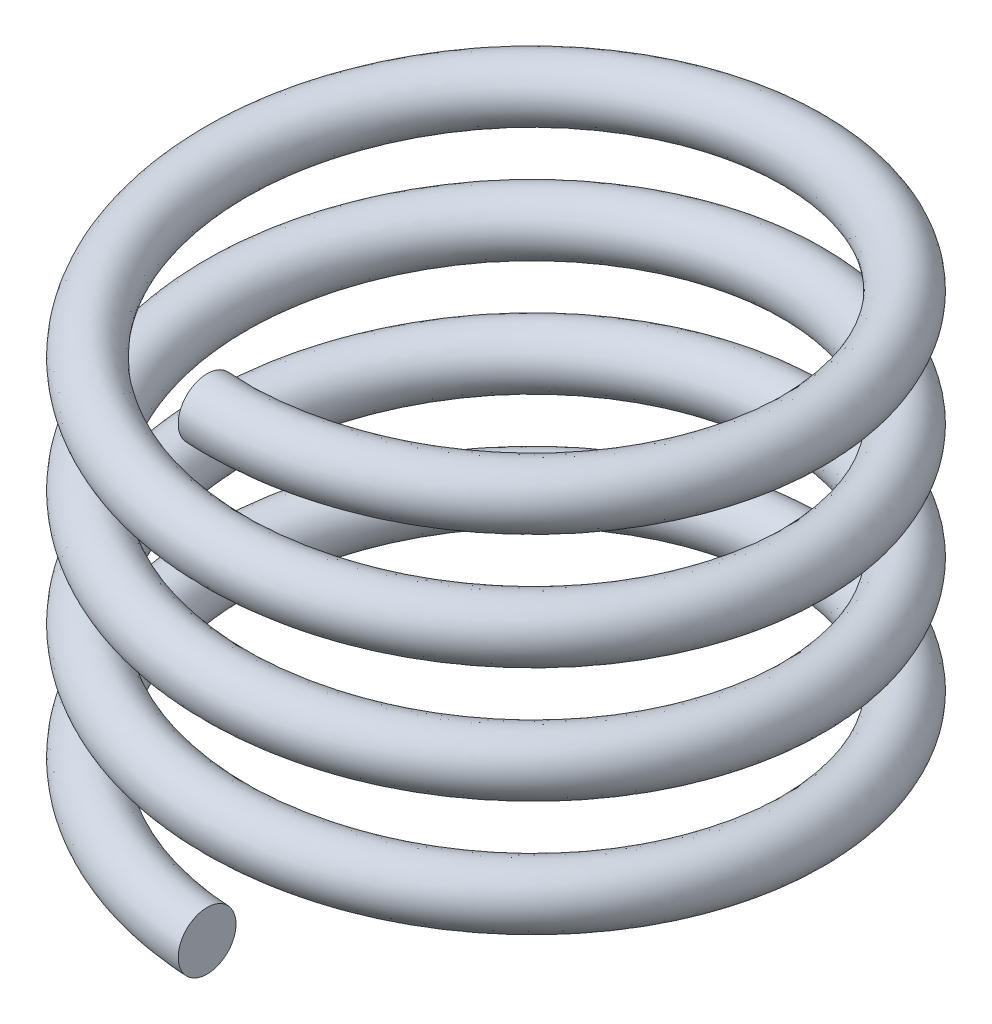
SolidWorks part; units mm, degrees
ref_plane "Front Plane" through (0, 0, 0) normal (0, 0, 1) x (1, 0, 0)
ref_plane "Top Plane" through (0, 0, 0) normal (0, 1, 0) x (1, 0, 0)
ref_plane "Right Plane" through (0, 0, 0) normal (1, 0, 0) x (0, 0, -1)
sketch "Sketch2" plane through (0, 0, 0) normal (0, 1, 0) x (1, 0, 0)
  circle A0 centre (0, 0) radius 6.35
  dimension "D1" = 12.7
curve "Helix/Spiral2" pitch 2.54 height 10.16 turns 4
sketch "Sketch3" plane through (0, 0, 0) normal (1, 0, 0) x (0, 0, -1)
  circle A0 centre (-6.35, 0) radius 0.635
  spline S0 degree 3 poles (-6.35, 0) (-6.35, 0.0526) (-6.0194, 0.1589) (-4.607, 0.3175) (-2.4933, 0.4763) (0, 0.635) (2.4933, 0.7938) (4.607, 0.9525) (6.0194, 1.1113) (6.5153, 1.27) (6.0194, 1.4288) (4.607, 1.5875) (1.7887, 1.7992) (-1.7887, 2.0108) (-4.607, 2.2225) (-6.0194, 2.3813) (-6.5153, 2.54) (-6.0194, 2.6988) (-4.607, 2.8575) (-1.7887, 3.0692) (1.7887, 3.2808) (4.607, 3.4925) (6.0194, 3.6513) (6.5153, 3.81) (6.0194, 3.9688) (4.607, 4.1275) (1.7887, 4.3392) (-1.7887, 4.5508) (-4.607, 4.7625) (-6.0194, 4.9212) (-6.5153, 5.08) (-6.0194, 5.2388) (-4.607, 5.3975) (-1.7887, 5.6092) (1.7887, 5.8208) (4.607, 6.0325) (6.0194, 6.1913) (6.5153, 6.35) (6.0194, 6.5087) (4.607, 6.6675) (1.7887, 6.8792) (-1.7887, 7.0908) (-4.607, 7.3025) (-6.0194, 7.4612) (-6.5153, 7.62) (-6.0194, 7.7787) (-4.607, 7.9375) (-1.7887, 8.1492) (1.7887, 8.3608) (4.607, 8.5725) (6.0194, 8.7312) (6.5153, 8.89) (6.0194, 9.0487) (4.607, 9.2075) (2.4933, 9.3662) (0, 9.525) (-2.4933, 9.6837) (-4.607, 9.8425) (-6.0194, 10.0011) (-6.35, 10.1074) (-6.35, 10.16) knots 0 0 0 0 0.015625 0.03125 0.046875 0.0625 0.078125 0.09375 0.109375 0.125 0.140625 0.15625 0.171875 0.203125 0.21875 0.234375 0.25 0.265625 0.28125 0.296875 0.328125 0.34375 0.359375 0.375 0.390625 0.40625 0.421875 0.453125 0.46875 0.484375 0.5 0.515625 0.53125 0.546875 0.578125 0.59375 0.609375 0.625 0.640625 0.65625 0.671875 0.703125 0.71875 0.734375 0.75 0.765625 0.78125 0.796875 0.828125 0.84375 0.859375 0.875 0.890625 0.90625 0.921875 0.9375 0.953125 0.96875 0.984375 1 1 1 1 construction
  dimension "D1" = 1.27
sweep "Sweep1" add profiles "Sketch3" path "Helix/Spiral2"
